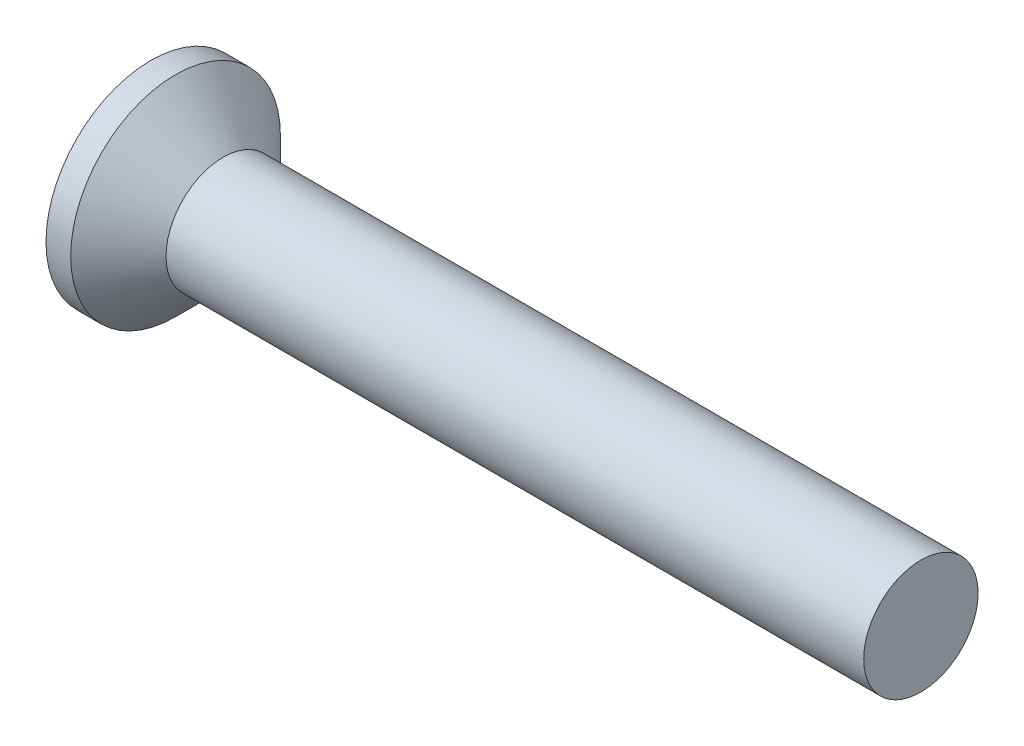
SolidWorks part; units mm, degrees
revolve "Base-Revolve" add sketch "BodySke" angle 360 about L4
sketch "BodySke" plane through (0, 0, 0) normal (0, 0, 1) x (1, 0, 0)
  line L0 (0, 0) -> (20.7277, 0)
  line L1 (20.7277, 0) -> (20.7277, 1.5)
  line L2 (20.7277, 1.5) -> (2.4277, 1.5)
  line L3 (2.4277, 1.5) -> (-7.1953, 11.123) construction
  line L4 (-15.875, 0) -> (82.55, 0) construction
  line L5 (2.4277, -1.5) -> (-7.1953, -11.123) construction
  line L6 (2.9277, 4.675) -> (2.9277, -11.2) construction
  line L7 (0.7277, 8.7375) -> (0.7277, -7.1375) construction
  line L8 (2.4277, 1.5) -> (1.1777, 2.75)
  line L9 (1.1777, 2.75) -> (0.53, 2.75)
  arc A0 (0, 0) -> (0.53, 2.75) centre (7.4, 0) cw
  arc A1 (0.7277, 3.2) -> (0, 0) centre (7.4, 0) ccw construction
  dimension "Crown_rad" = 7.4
  dimension "Diameter" = 3
  dimension "Advance" = 0.5
  dimension "Thread_nom" = 20
  dimension "Head_ang" = 90
  dimension "D3" = 6.4
  dimension "Side_ht" = 1.7
  dimension "D4" = 0.7277
  dimension "Length" = 20
  dimension "Head_dia" = 5.5
cosmetic thread "ThreadCosmetic" [suppressed] parameters "Thread_length"=17.8, "Thread_minor"=2.439
ref_plane "Plane1" through (0, 0, 0) normal (0, 0, 1) x (1, 0, 0)
ref_plane "Plane2" through (0, 0, 0) normal (0, 1, 0) x (1, 0, 0)
ref_plane "Plane3" through (0, 0, 0) normal (1, 0, 0) x (0, 0, -1)
sketch "Sketch2" plane through (0, 0, 0) normal (1, 0, 0) x (0, 0, -1)
  line L0 (2.75, -0.5) -> (-2.75, -0.5)
  line L1 (2.75, -0.5) -> (2.75, 0.5)
  line L2 (-2.75, 0.5) -> (2.75, 0.5)
  line L3 (-2.75, 0.5) -> (-2.75, -0.5)
  dimension "D1" = 5.5
  dimension "Slot_width" = 1
  dimension "D3" = 2.75
  dimension "D4" = 0.5
extrude "Slot" [suppressed] cut sketch "Sketch2" along normal blind 1.5
sketch "Sketch3" plane through (0, 0, 0) normal (1, 0, 0) x (0, 0, -1)
  line L0 (0.415, -1.72) -> (-0.415, -1.72)
  line L1 (0.415, -1.72) -> (0.415, 1.72)
  line L2 (-0.415, 1.72) -> (0.415, 1.72)
  line L3 (-0.415, 1.72) -> (-0.415, -1.72)
  dimension "Cross_width" = 0.83
  dimension "D1" = 0.415
  dimension "Cross_dia" = 3.44
  dimension "D2" = 1.72
ref_plane "Plane4" through (2.33, 0, 0) normal (1, 0, 0) x (0, 0, -1)
sketch "Sketch4" plane through (2.33, 0, 0) normal (1, 0, 0) x (0, 0, -1)
  line L0 (0.2075, -0.2075) -> (-0.2075, -0.2075)
  line L1 (0.2075, -0.2075) -> (0.2075, 0.2075)
  line L2 (-0.2075, 0.2075) -> (0.2075, 0.2075)
  line L3 (-0.2075, 0.2075) -> (-0.2075, -0.2075)
  dimension "D1" = 0.415
  dimension "D2" = 0.415
  dimension "D3" = 0.2075
  dimension "D4" = 0.2075
loft "Cross" cut profiles "Sketch3", "Sketch4"
pattern_circular "CirPattern1" count 2 every 90 about axis through (0, 0, 0) along (1, 0, 0) of "Cross"
sketch "ThdSchSke" plane through (0, 0, 0) normal (0, 0, 1) x (1, 0, 0)
  line L0 (2.9277, -1.2195) -> (2.7313, -1.5)
  line L1 (2.9277, -1.2195) -> (3.1241, -1.5)
  line L2 (3.1241, -1.5) -> (3.1241, -1.875)
  line L3 (-3.175, 0) -> (5.1513, 0) construction
  line L5 (3.1241, -1.875) -> (2.7313, -1.875)
  line L6 (2.7313, -1.875) -> (2.7313, -1.5)
  line L8 (20.7277, -1.5) -> (20.7277, 1.5) construction
  dimension "Diameter" = 3
  dimension "Thread_minor" = 2.439
  dimension "Start" = 17.8
revolve "ThreadSchematic" [suppressed] cut sketch "ThdSchSke" angle 360 about L3
pattern_linear "ThdSchPat" [suppressed]
equation "\"D1@Sketch2\" = \"Head_dia@BodySke\""
equation "\"D3@Sketch2\" = \"D1@Sketch2\" / 2"
equation "\"D4@Sketch2\" = \"Slot_width@Sketch2\" / 2"
equation "\"D1@Sketch3\" = \"Cross_width@Sketch3\" / 2"
equation "\"D2@Sketch3\" = \"Cross_dia@Sketch3\" / 2"
equation "\"D1@Sketch4\" = \"Cross_width@Sketch3\"*.5"
equation "\"D2@Sketch4\" = \"D1@Sketch4\""
equation "\"D3@Sketch4\" = \"D1@Sketch4\" / 2"
equation "\"D4@Sketch4\" = \"D2@Sketch4\" / 2"
equation "\"Thread_length@ThreadCosmetic\" = ((sgn( (\"Length@BodySke\" - \"Advance@BodySke\" - \"Side_ht@BodySke\" ) - \"Thread_nom@BodySke\" )-1)*( (\"Length@BodySke\" - \"Advance@BodySke\" - \"Side_ht@BodySke\" ) - \"Thread_nom@BodySke\" ))/-2+ \"Thread_nom@BodySke\""
equation "\"Thread_minor@ThdSchSke\" = \"Thread_minor@ThreadCosmetic\""
equation "\"Diameter@ThdSchSke\" = \"Diameter@BodySke\""
equation "\"Overcut@ThdSchSke\" = \"Diameter@BodySke\" * 1.25"
equation "\"Start@ThdSchSke\" =  \"Thread_length@ThreadCosmetic\""
equation "\"Num_threads@ThdSchPat\" = int( \"Thread_length@ThreadCosmetic\" / \"Advance@BodySke\" + 0.999 )  + 1"
equation "\"Advance@ThdSchPat\" = \"Thread_length@ThreadCosmetic\" /  (\"Num_threads@ThdSchPat\" - 1) 'relax it"
